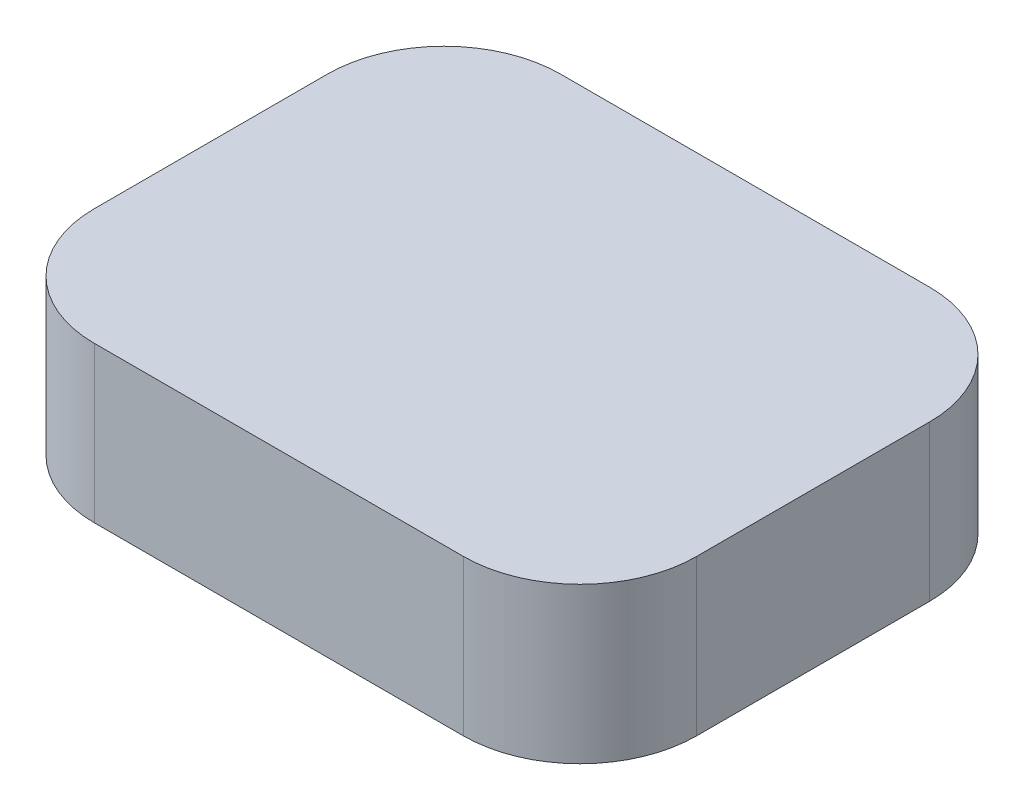
SolidWorks part; units mm, degrees
ref_plane "Front Plane" through (0, 0, 0) normal (0, 0, 1) x (1, 0, 0)
ref_plane "Top Plane" through (0, 0, 0) normal (0, 1, 0) x (1, 0, 0)
ref_plane "Right Plane" through (0, 0, 0) normal (1, 0, 0) x (0, 0, -1)
sketch "Sketch1" plane through (0, 0, 0) normal (0, 1, 0) x (1, 0, 0)
  line L1 (-15.5, -12) -> (15.5, -12)
  line L2 (-15.5, -12) -> (-15.5, 12)
  line L3 (-15.5, 12) -> (15.5, 12)
  line L4 (15.5, -12) -> (15.5, 12)
  line L5 (-15.5, -12) -> (15.5, 12) construction
  line L6 (-15.5, 12) -> (15.5, -12) construction
  point P0 (0, 0)
  dimension "D1" = 31
  dimension "D2" = 24
extrude "Boss-Extrude1" add sketch "Sketch1" along normal blind 8
fillet "Fillet1" radius 6 4 edges at (-15.5, 4, -12) (-15.5, 4, 12) (15.5, 4, -12) (15.5, 4, 12)
